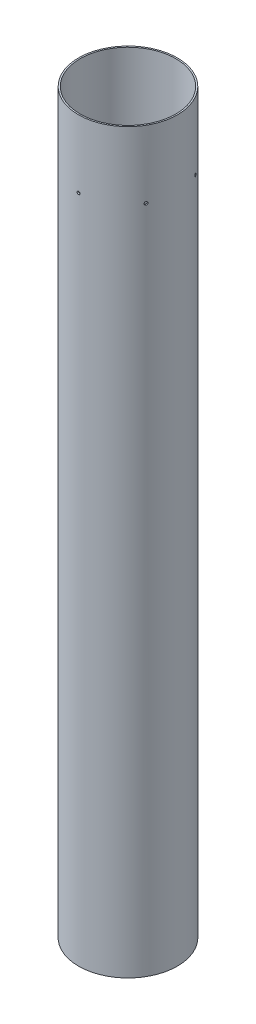
SolidWorks part; units mm, degrees
ref_plane "Front Plane" through (0, 0, 0) normal (0, 0, 1) x (1, 0, 0)
ref_plane "Top Plane" through (0, 0, 0) normal (0, 1, 0) x (1, 0, 0)
ref_plane "Right Plane" through (0, 0, 0) normal (1, 0, 0) x (0, 0, -1)
sketch "Sketch1" plane through (0, 0, 0) normal (0, 1, 0) x (1, 0, 0)
  circle A0 centre (0, 0) radius 51.054
  circle A1 centre (0, 0) radius 49.53
  dimension "D1" = 99.06
  dimension "D2" = 102.108
extrude "Boss-Extrude1" add sketch "Sketch1" along normal blind 762
sketch "Sketch2" plane through (0, 0, 0) normal (0, 0, 1) x (1, 0, 0)
  line L0 (0, 762) -> (0, 693.674)
  line L1 (51.054, 762) -> (-51.054, 762) construction
  line L2 (0, 693.674) -> (0, 692.15)
  circle A0 centre (0, 692.15) radius 1.524
  dimension "D2" = 3.048
  dimension "D1" = 68.326
extrude "Cut-Extrude1" cut sketch "Sketch2" against normal blind 66.04
pattern_circular "CirPattern1" count 6 over 360 about axis through (0, 762, 0) along (0, -1, 0) of "Cut-Extrude1"
